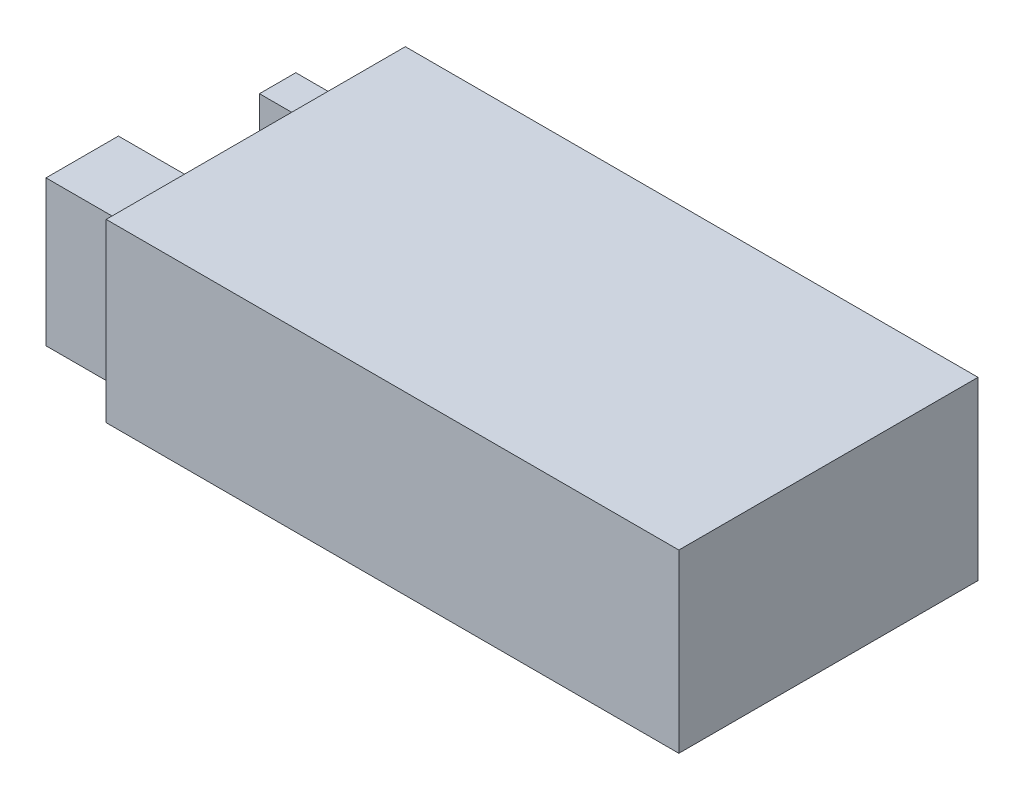
SolidWorks part; units mm, degrees
ref_plane "Front Plane" through (0, 0, 0) normal (0, 0, 1) x (1, 0, 0)
ref_plane "Top Plane" through (0, 0, 0) normal (0, 1, 0) x (1, 0, 0)
ref_plane "Right Plane" through (0, 0, 0) normal (1, 0, 0) x (0, 0, -1)
sketch "Sketch1" plane through (0, 0, 0) normal (0, 1, 0) x (1, 0, 0)
  line L1 (-33.5, 17.5) -> (33.5, 17.5)
  line L2 (-33.5, 17.5) -> (-33.5, -17.5)
  line L3 (-33.5, -17.5) -> (33.5, -17.5)
  line L4 (33.5, 17.5) -> (33.5, -17.5)
  line L5 (-33.5, 17.5) -> (33.5, -17.5) construction
  line L6 (-33.5, -17.5) -> (33.5, 17.5) construction
  point P0 (0, 0)
  dimension "D1" = 35
  dimension "D2" = 67
extrude "Boss-Extrude1" add sketch "Sketch1" along normal blind 20.6
sketch "Sketch2" plane through (-33.5, 0, 0) normal (-1, 0, 0) x (0, 0, 1)
  line L1 (-14.6878, 4.0845) -> (-10.4331, 4.0845)
  line L2 (-14.6878, 4.0845) -> (-14.6878, 14.3697)
  line L3 (-14.6878, 14.3697) -> (-10.4331, 14.3697)
  line L4 (-10.4331, 4.0845) -> (-10.4331, 14.3697)
  line L5 (6.0675, 1.3097) -> (14.5398, 1.3097)
  line L6 (6.0675, 1.3097) -> (6.0675, 18.3283)
  line L7 (6.0675, 18.3283) -> (14.5398, 18.3283)
  line L8 (14.5398, 1.3097) -> (14.5398, 18.3283)
extrude "Boss-Extrude2" add sketch "Sketch2" along normal blind 10
